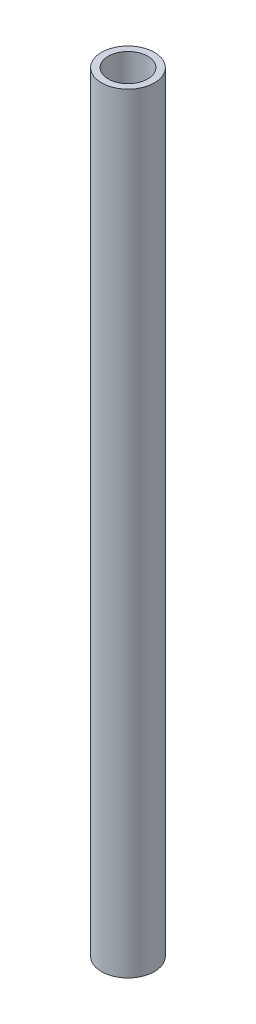
SolidWorks part; units mm, degrees
material "AISI 321 Annealed Stainless Steel (SS)"
ref_plane "Front Plane" through (0, 0, 0) normal (0, 0, 1) x (1, 0, 0)
ref_plane "Top Plane" through (0, 0, 0) normal (0, 1, 0) x (1, 0, 0)
ref_plane "Right Plane" through (0, 0, 0) normal (1, 0, 0) x (0, 0, -1)
sketch "Sketch1" plane through (0, 0, 0) normal (0, 1, 0) x (1, 0, 0)
  circle A0 centre (0, 0) radius 3.95
  circle A1 centre (0, 0) radius 2.95
  dimension "D1" = 7.9
  dimension "D2" = 1
extrude "Boss-Extrude1" add sketch "Sketch1" along normal blind 115
